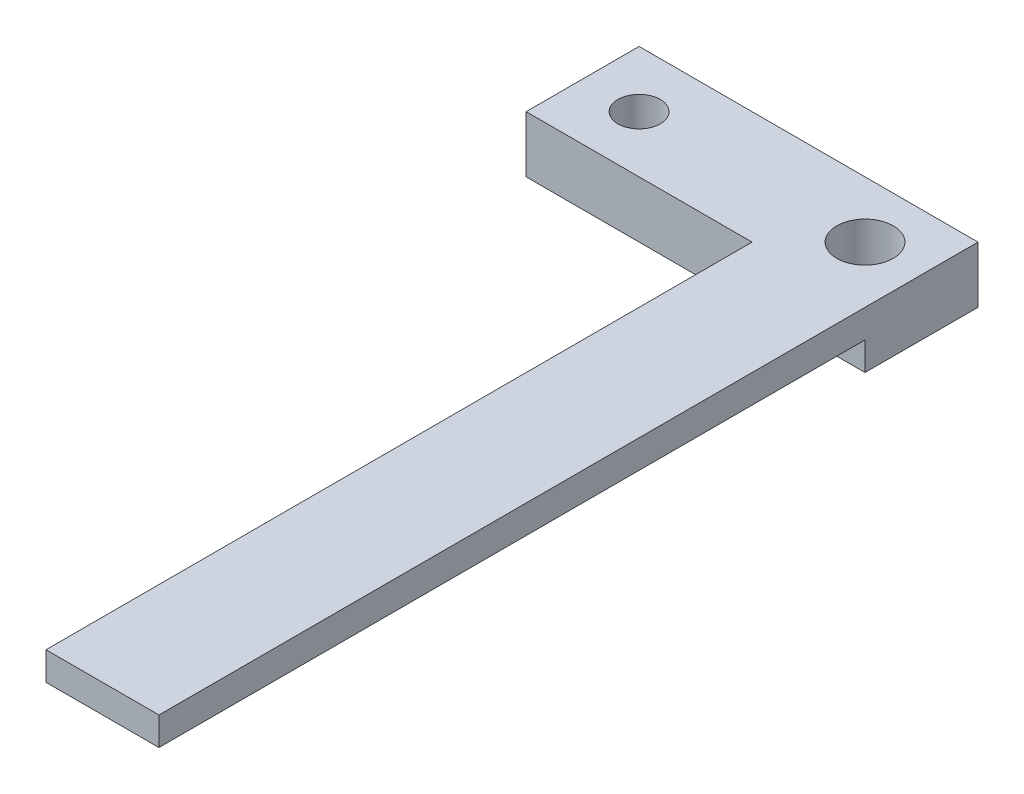
SolidWorks part; units mm, degrees
ref_plane "Front Plane" through (0, 0, 0) normal (0, 0, 1) x (1, 0, 0)
ref_plane "Top Plane" through (0, 0, 0) normal (0, 1, 0) x (1, 0, 0)
ref_plane "Right Plane" through (0, 0, 0) normal (1, 0, 0) x (0, 0, -1)
sketch "Sketch1" plane through (0, 0, 0) normal (0, 1, 0) x (1, 0, 0)
  line L1 (-60, -20) -> (60, -20)
  line L2 (-60, -20) -> (-60, 20)
  line L3 (-60, 20) -> (60, 20)
  line L4 (60, -20) -> (60, 20)
  line L5 (-60, -20) -> (60, 20) construction
  line L6 (-60, 20) -> (60, -20) construction
  circle A0 centre (-40, 0) radius 7.5
  circle A1 centre (40, 0) radius 10
  point P0 (0, 0)
  dimension "D1" = 15
  dimension "D2" = 20
  dimension "D6" = 40
  dimension "D3" = 40
  dimension "D4" = 80
  dimension "D5" = 120
extrude "Boss-Extrude1" add sketch "Sketch1" along normal blind 20
sketch "Sketch2" plane through (0, 0, 0) normal (0, -1, 0) x (1, 0, 0)
  circle A0 centre (-40, 0) radius 10
  circle A1 centre (-40, 0) radius 7.5 construction
  circle A2 centre (-40, 0) radius 7.5
  dimension "D1" = 20
extrude "Boss-Extrude2" add sketch "Sketch2" along normal blind 10
sketch "Sketch3" plane through (0, 0, 20) normal (0, 0, 1) x (1, 0, 0)
  line L1 (20, 10) -> (60, 10)
  line L2 (20, 10) -> (20, 20)
  line L3 (20, 20) -> (60, 20)
  line L4 (60, 10) -> (60, 20)
  line L5 (20, 10) -> (60, 20) construction
  line L6 (20, 20) -> (60, 10) construction
  point P0 (40, 15)
  dimension "D1" = 40
  dimension "D2" = 10
extrude "Boss-Extrude3" add sketch "Sketch3" along normal blind 250
